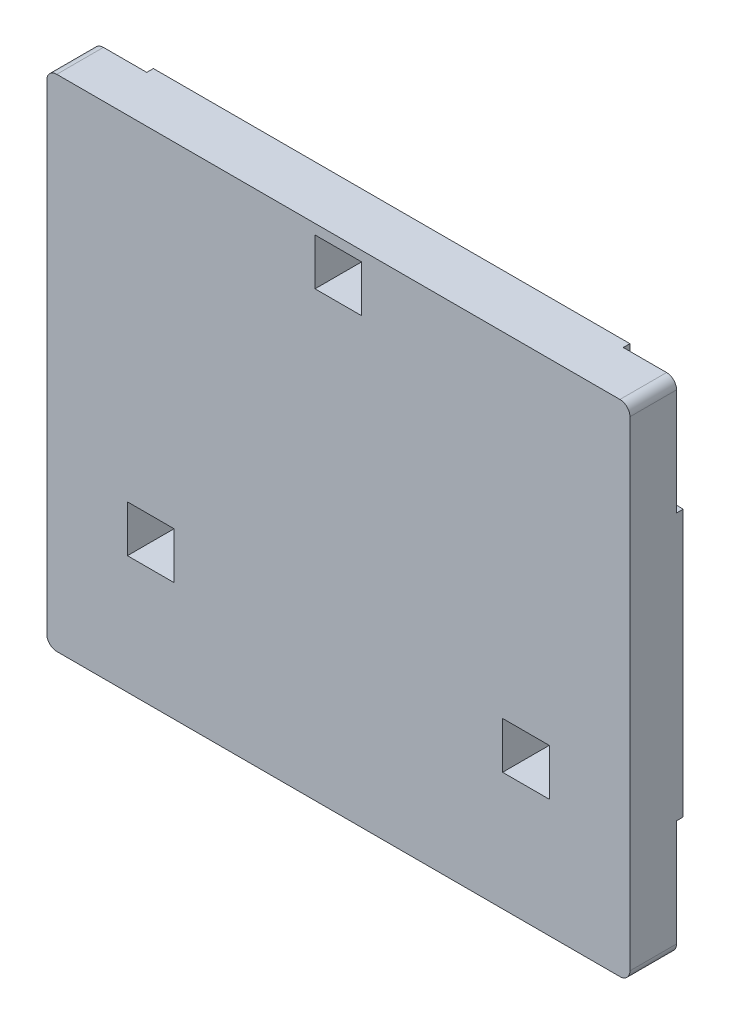
SolidWorks part; units mm, degrees
ref_plane "Front Plane" through (0, 0, 0) normal (0, 0, 1) x (1, 0, 0)
ref_plane "Top Plane" through (0, 0, 0) normal (0, 1, 0) x (1, 0, 0)
ref_plane "Right Plane" through (0, 0, 0) normal (1, 0, 0) x (0, 0, -1)
sketch "Sketch1" plane through (0, 0, 0) normal (0, 0, 1) x (1, 0, 0)
  line L1 (0, 0) -> (-175, 0)
  line L2 (0, 0) -> (0, -150)
  line L3 (0, -150) -> (-175, -150)
  line L4 (-175, 0) -> (-175, -150)
  dimension "D1" = 175
  dimension "D2" = 150
extrude "Boss-Extrude1" add sketch "Sketch1" along normal blind 16
sketch "Sketch2" plane through (0, 0, 16) normal (0, 0, 1) x (1, 0, 0)
  line L0 (-87.5, 0) -> (-87.5, -150) construction
  line L1 (0, 0) -> (-175, 0) construction
  line L2 (-175, -150) -> (0, -150) construction
  line L3 (-175, -75) -> (0, -75) construction
  line L4 (-87.5, -10) -> (-143.7917, -107.5) construction
  line L5 (0, -150) -> (0, 0) construction
  line L6 (-175, 0) -> (-175, -150) construction
  line L7 (-87.5, -10) -> (-31.2083, -107.5) construction
  line L8 (-143.7917, -107.5) -> (-31.2083, -107.5) construction
  line L10 (-80.5, -3) -> (-94.5, -3)
  line L11 (-80.5, -3) -> (-80.5, -17)
  line L12 (-80.5, -17) -> (-94.5, -17)
  line L13 (-94.5, -3) -> (-94.5, -17)
  line L14 (-80.5, -3) -> (-94.5, -17) construction
  line L15 (-80.5, -17) -> (-94.5, -3) construction
  line L16 (-136.7917, -114.5) -> (-150.7917, -114.5)
  line L17 (-136.7917, -114.5) -> (-136.7917, -100.5)
  line L18 (-136.7917, -100.5) -> (-150.7917, -100.5)
  line L19 (-150.7917, -114.5) -> (-150.7917, -100.5)
  line L20 (-136.7917, -114.5) -> (-150.7917, -100.5) construction
  line L21 (-136.7917, -100.5) -> (-150.7917, -114.5) construction
  line L22 (-24.2083, -114.5) -> (-38.2083, -114.5)
  line L23 (-24.2083, -114.5) -> (-24.2083, -100.5)
  line L24 (-24.2083, -100.5) -> (-38.2083, -100.5)
  line L25 (-38.2083, -114.5) -> (-38.2083, -100.5)
  line L26 (-24.2083, -114.5) -> (-38.2083, -100.5) construction
  line L27 (-24.2083, -100.5) -> (-38.2083, -114.5) construction
  circle A0 centre (-143.7917, -107.5) radius 7.5 construction
  circle A1 centre (-87.5, -10) radius 7.5 construction
  circle A2 centre (-31.2083, -107.5) radius 7.5 construction
  circle A4 centre (-87.5, -75) radius 65 construction
  point P32 (0, 0)
  dimension "D1" = 15
  dimension "D2" = 130
  dimension "D3" = 14
  dimension "D4" = 14
  dimension "D5" = 14
  dimension "D6" = 14
  dimension "D7" = 14
  dimension "D8" = 14
extrude "Cut-Extrude1" cut sketch "Sketch2" against normal blind 14
sketch "Sketch4" plane through (0, 0, 0) normal (0, 0, -1) x (-1, 0, 0)
  line L1 (175, 0) -> (159, 0)
  line L2 (175, 0) -> (175, -35)
  line L3 (175, -35) -> (159, -35)
  line L4 (159, 0) -> (159, -35)
  line L5 (175, -150) -> (159, -150)
  line L6 (175, -150) -> (175, -115)
  line L7 (175, -115) -> (159, -115)
  line L8 (159, -150) -> (159, -115)
  line L9 (0, -150) -> (16, -150)
  line L10 (0, -150) -> (0, -115)
  line L11 (0, -115) -> (16, -115)
  line L12 (16, -150) -> (16, -115)
  line L13 (0, 0) -> (16, 0)
  line L14 (0, 0) -> (0, -35)
  line L15 (0, -35) -> (16, -35)
  line L16 (16, 0) -> (16, -35)
  dimension "D1" = 35
  dimension "D2" = 16
extrude "Cut-Extrude5" cut sketch "Sketch4" against normal blind 2
fillet "Fillet1" radius 3 4 edges at (0, 0, 9) (0, -150, 9) (-175, -150, 9) (-175, 0, 9)
